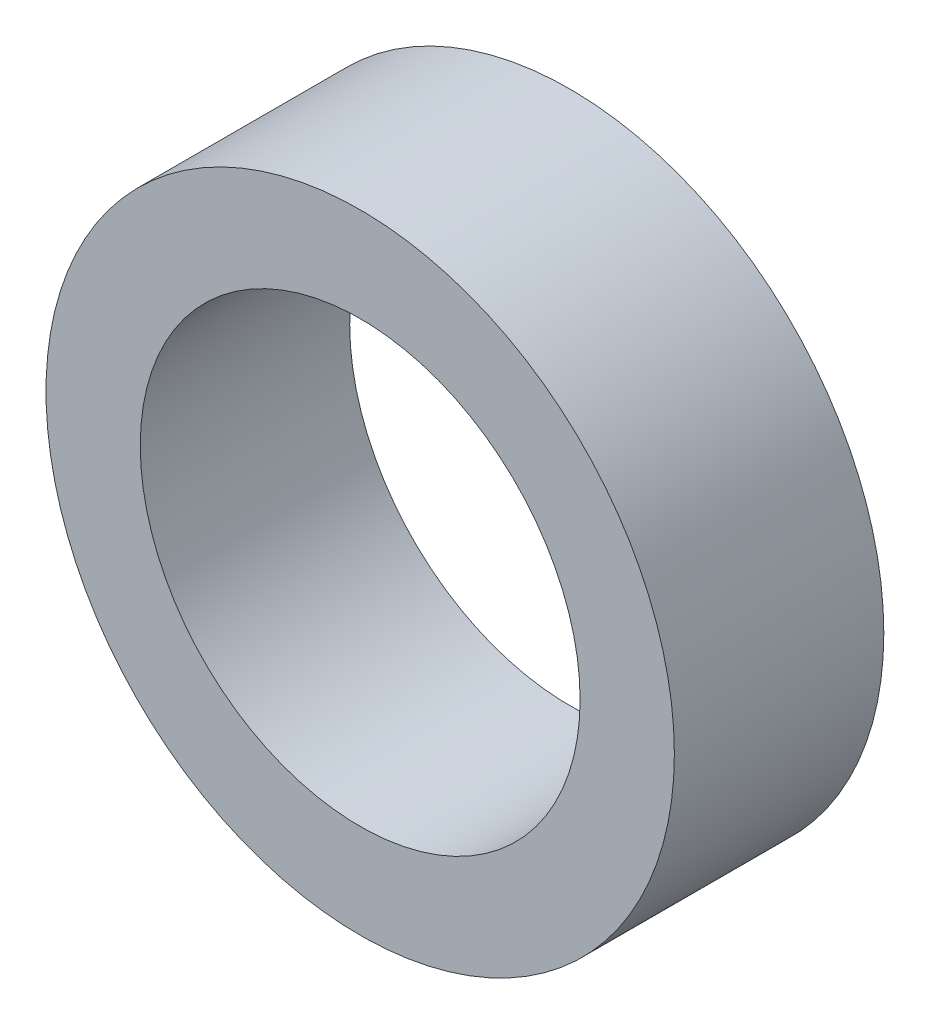
SolidWorks part; units mm, degrees
ref_plane "Front Plane" through (0, 0, 0) normal (0, 0, 1) x (1, 0, 0)
ref_plane "Top Plane" through (0, 0, 0) normal (0, 1, 0) x (1, 0, 0)
ref_plane "Right Plane" through (0, 0, 0) normal (1, 0, 0) x (0, 0, -1)
sketch "Sketch1" plane through (0, 0, 0) normal (0, 0, 1) x (1, 0, 0)
  circle A0 centre (0, 0) radius 5.25
  circle A1 centre (0, 0) radius 7.5
  dimension "D1" = 10.5
  dimension "D2" = 15
extrude "Boss-Extrude1" add sketch "Sketch1" along normal blind 5
